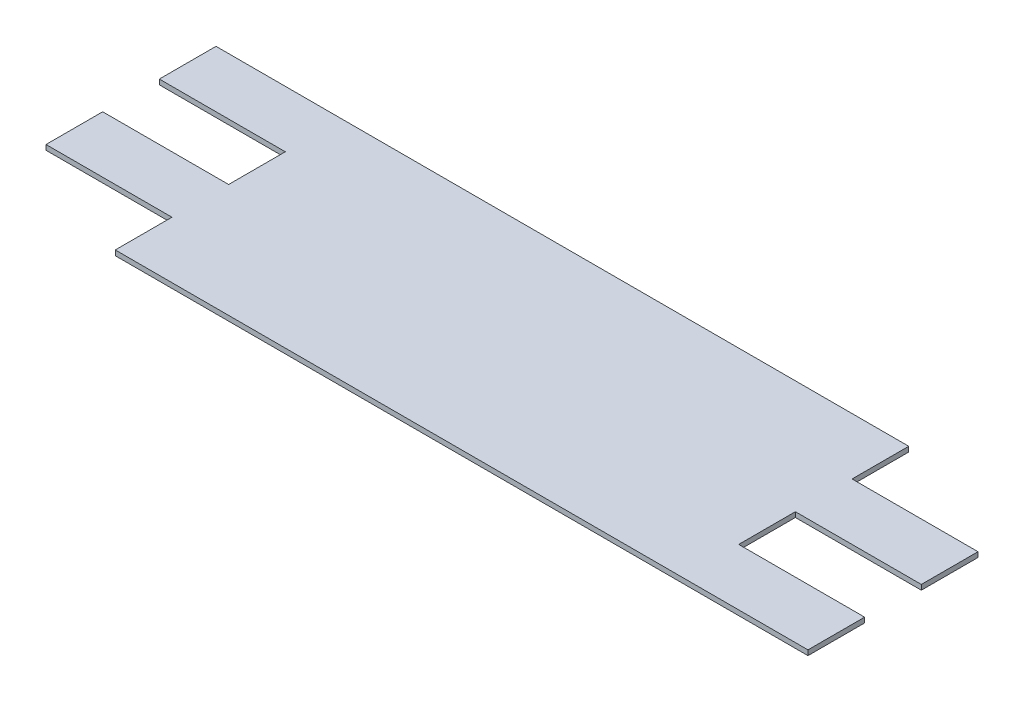
SolidWorks part; units mm, degrees
ref_plane "Front Plane" through (0, 0, 0) normal (0, 0, 1) x (1, 0, 0)
ref_plane "Top Plane" through (0, 0, 0) normal (0, 1, 0) x (1, 0, 0)
ref_plane "Right Plane" through (0, 0, 0) normal (1, 0, 0) x (0, 0, -1)
sketch "Sketch1" plane through (0, 0, 0) normal (0, 1, 0) x (1, 0, 0)
  line L0 (0, 0) -> (55, 0)
  line L2 (65, -18) -> (10, -18)
  line L10 (0, 0) -> (0, -4.5)
  line L11 (0, -4.5) -> (10, -4.5)
  line L12 (10, -4.5) -> (10, -9)
  line L13 (10, -9) -> (0, -9)
  line L14 (0, -9) -> (0, -13.5)
  line L15 (0, -13.5) -> (10, -13.5)
  line L16 (10, -13.5) -> (10, -18)
  line L17 (55, 0) -> (55, -4.5)
  line L18 (10, -18) -> (0, -18) [skipped]
  line L19 (55, -4.5) -> (65, -4.5)
  line L20 (65, -4.5) -> (65, -9)
  line L21 (65, -9) -> (55, -9)
  line L22 (55, -9) -> (55, -13.5)
  line L23 (55, -13.5) -> (65, -13.5)
  line L24 (65, -13.5) -> (65, -18)
  point P3 (66.509, -18)
  point P14 (11.5641, -18)
  point P16 (54.5951, 0)
  dimension "D1" = 2
  dimension "D2" = 4.5
  dimension "D4" = 18
  dimension "D5" = 55
  dimension "D3" = 10
extrude "Boss-Extrude1" add sketch "Sketch1" along normal blind 0.4
